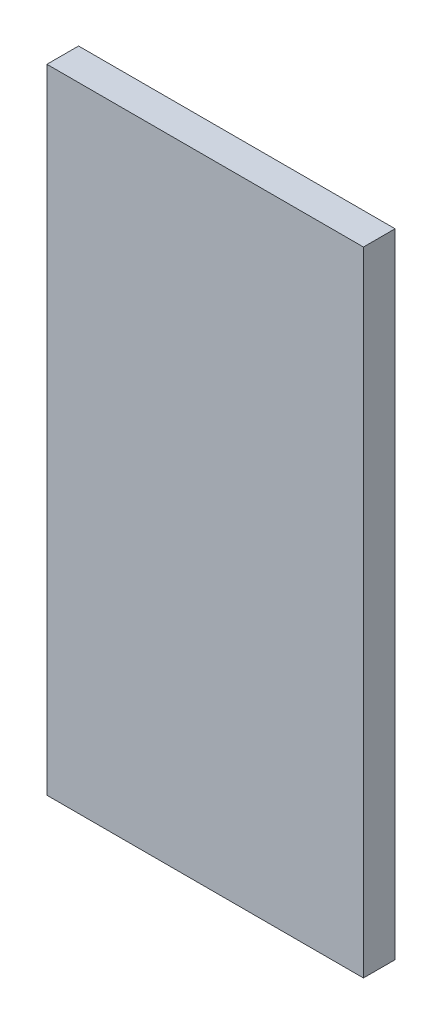
SolidWorks part; units mm, degrees
ref_plane "Plan de face" through (0, 0, 0) normal (0, 0, 1) x (1, 0, 0)
ref_plane "Plan de dessus" through (0, 0, 0) normal (0, 1, 0) x (1, 0, 0)
ref_plane "Plan de droite" through (0, 0, 0) normal (1, 0, 0) x (0, 0, -1)
sketch "Esquisse1" plane through (0, 0, 0) normal (0, 0, 1) x (1, 0, 0)
  line L1 (-50, -100) -> (50, -100)
  line L2 (-50, -100) -> (-50, 100)
  line L3 (-50, 100) -> (50, 100)
  line L4 (50, -100) -> (50, 100)
  line L5 (-50, -100) -> (50, 100) construction
  line L6 (-50, 100) -> (50, -100) construction
  point P0 (0, 0)
  dimension "D1" = 100
  dimension "D2" = 200
extrude "Boss.-Extru.1" add sketch "Esquisse1" along normal blind 10
